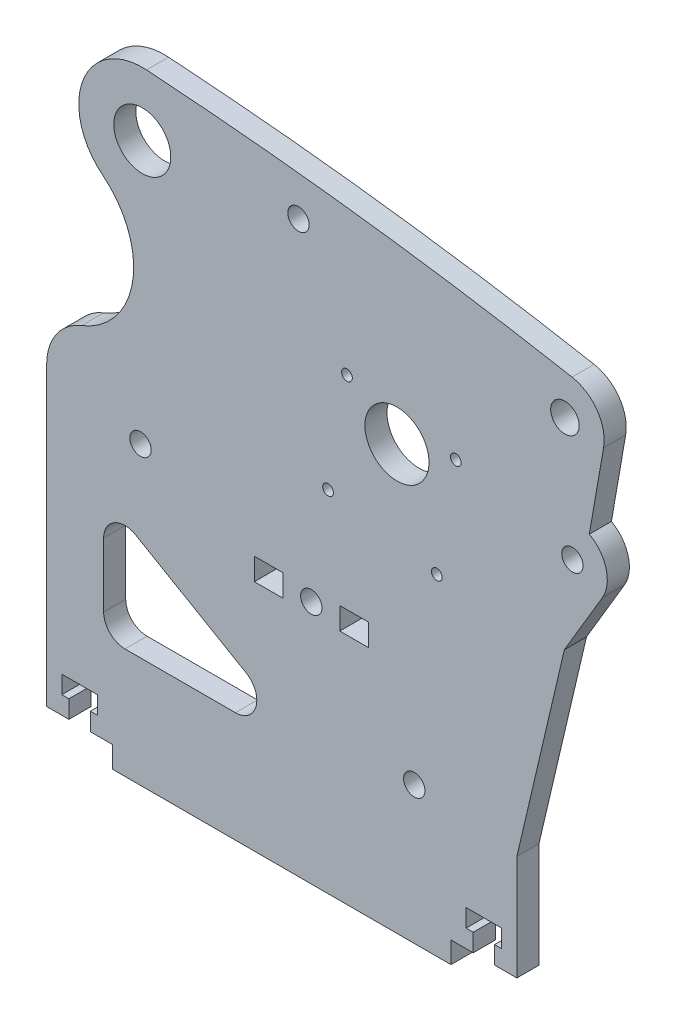
SolidWorks part; units mm, degrees
ref_plane "Front Plane" through (0, 0, 0) normal (0, 0, 1) x (1, 0, 0)
ref_plane "Top Plane" through (0, 0, 0) normal (0, 1, 0) x (1, 0, 0)
ref_plane "Right Plane" through (0, 0, 0) normal (1, 0, 0) x (0, 0, -1)
sketch "Sketch1" plane through (0, 0, 0) normal (0, 0, 1) x (1, 0, 0)
  line L0 (33.65, -83.5) -> (47, -26.5)
  line L1 (-98.35, -29.9005) -> (-98.35, -113)
  line L2 (58, 28.0717) -> (54, 5.0717)
  line L4 (15.15, -113) -> (15.15, -119)
  line L5 (57.6783, -8.5) -> (47, -26.5)
  line L6 (15.15, -119) -> (-79.85, -119)
  line L7 (33.65, -83.5) -> (33.65, -113)
  line L8 (33.65, -113) -> (15.15, -113)
  line L9 (-79.85, -119) -> (-79.85, -113)
  line L10 (-79.85, -113) -> (-98.35, -113)
  line L11 (-79.85, -113) -> (-98.35, -113)
  line L12 (-82.35, -64) -> (-82.35, -82)
  line L13 (-76.35, -88) -> (-45.35, -88)
  line L14 (-42.3372, -76.8113) -> (-73.3372, -58.8113)
  line L20 (57.6783, -8.5) -> (47, -26.5)
  line L22 (33.65, -83.5) -> (33.65, -113)
  line L23 (33.65, -113) -> (15.15, -113)
  line L27 (-82.35, -64) -> (-82.35, -82)
  line L28 (-76.35, -88) -> (-45.35, -88)
  line L29 (-42.3372, -76.8113) -> (-73.3372, -58.8113)
  circle A0 centre (47.15, 30) radius 4
  circle A1 centre (-71.5, 38) radius 8
  circle A2 centre (-71.5, 38) radius 3.5
  circle A3 centre (-27.65, 40.9) radius 3
  circle A4 centre (4.85, -80.4) radius 3
  circle A5 centre (49.25, -3.5) radius 3
  circle A6 centre (-72, -36) radius 3
  circle A7 centre (0, 0) radius 9
  circle A8 centre (0, 0) radius 18.05 construction
  circle A9 centre (47.15, 30) radius 4
  circle A10 centre (-71.5, 38) radius 8
  circle A11 centre (-71.5, 38) radius 3.5
  circle A12 centre (-27.65, 40.9) radius 3
  circle A13 centre (4.85, -80.4) radius 3
  circle A14 centre (49.25, -3.5) radius 3
  circle A15 centre (-72, -36) radius 3
  circle A16 centre (0, 0) radius 9
  circle A17 centre (0, 0) radius 18.05 construction
  arc A18 (58, 28.0717) -> (49.1523, 40.8366) centre (47.15, 30) ccw
  arc A19 (57.6783, -8.5) -> (54, 5.0717) centre (49.25, -3.5) ccw
  arc A21 (-88.5337, -15.4802) -> (-98.35, -29.9005) centre (-82.85, -29.9005) ccw
  arc A22 (-88.5337, -15.4802) -> (-82.6112, 24.0566) centre (-97, 6) ccw
  arc A23 (-70.3185, 55.7899) -> (-82.6112, 24.0566) centre (-71.5, 38) ccw
  arc A24 (-70.3185, 55.7899) -> (49.1523, 40.8366) centre (-138.9064, -976.935) cw
  arc A25 (-73.3372, -58.8113) -> (-82.35, -64) centre (-76.35, -64) ccw
  arc A26 (-82.35, -82) -> (-76.35, -88) centre (-76.35, -82) ccw
  arc A27 (-45.35, -88) -> (-42.3372, -76.8113) centre (-45.35, -82) ccw
  arc A28 (58, 28.0717) -> (49.1523, 40.8366) centre (47.15, 30) ccw
  arc A29 (57.6783, -8.5) -> (54, 5.0717) centre (49.25, -3.5) ccw
  arc A31 (-88.5337, -15.4802) -> (-98.35, -29.9005) centre (-82.85, -29.9005) ccw
  arc A32 (-88.5337, -15.4802) -> (-82.6112, 24.0566) centre (-97, 6) ccw
  arc A33 (-70.3185, 55.7899) -> (-82.6112, 24.0566) centre (-71.5, 38) ccw
  arc A35 (-73.3372, -58.8113) -> (-82.35, -64) centre (-76.35, -64) ccw
  arc A36 (-82.35, -82) -> (-76.35, -88) centre (-76.35, -82) ccw
  arc A37 (-45.35, -88) -> (-42.3372, -76.8113) centre (-45.35, -82) ccw
  point P0 (-98.35, -71.4503)
  dimension "D1" = 18
  dimension "D2" = 47.15
  dimension "D3" = 30
  dimension "D4" = 8
  dimension "D5" = 36
  dimension "D6" = 72
  dimension "D7" = 6
  dimension "D8" = 49.25
  dimension "D9" = 3.5
  dimension "D10" = 40.9
  dimension "D11" = 27.65
  dimension "D12" = 80.4
  dimension "D13" = 4.85
  dimension "D23" = 7
  dimension "D24" = 16
  dimension "D27" = 15.5
  dimension "D32" = 1035
  dimension "D35" = 6
  dimension "D14" = 113
  dimension "D15" = 132
  dimension "D16" = 33.65
  dimension "D17" = 83.5
  dimension "D18" = 47
  dimension "D19" = 57
  dimension "D20" = 83.0995
  dimension "D21" = 71.5
  dimension "D22" = 38
  dimension "D25" = 97
  dimension "D26" = 6
  dimension "D28" = 18
  dimension "D29" = 23
  dimension "D30" = 54
  dimension "D31" = 58
  dimension "D33" = 16
  dimension "D34" = 25
  dimension "D36" = 31
  dimension "D37" = 18
  dimension "D38" = 95
  dimension "D39" = 6
  dimension "D40" = 18.5
extrude "Boss-Extrude1" add sketch "Sketch1" along normal blind 6.2
ref_plane "Plane1" through (-32.35, 0, 0) normal (-1, 0, 0) x (0, 0, 1)
sketch "Sketch2" plane through (0, 0, 6.2) normal (0, 0, 1) x (1, 0, 0)
  circle A0 centre (-19.3487, -20.7923) radius 1.5 construction
  circle A1 centre (11.1929, -26.1038) radius 1.5 construction
  circle A2 centre (-14.0371, 9.7493) radius 1.5 construction
  circle A3 centre (16.5044, 4.4377) radius 1.5 construction
  circle A4 centre (-19.3487, -20.7923) radius 1.5
  circle A5 centre (11.1929, -26.1038) radius 1.5
  circle A6 centre (-14.0371, 9.7493) radius 1.5
  circle A7 centre (16.5044, 4.4377) radius 1.5
extrude "Cut-Extrude1" cut sketch "Sketch2" against normal up to next
sketch "Sketch3" plane through (0, 0, 0) normal (0, 0, -1) x (-1, 0, 0)
  line L0 (-29.4, -103) -> (-19.4, -103)
  line L1 (-29.4, -103) -> (-29.4, -108)
  line L2 (-29.4, -108) -> (-27.4, -108)
  line L3 (-19.4, -103) -> (-19.4, -108)
  line L4 (-33.65, -113) -> (-15.15, -113) construction
  line L10 (-21.4, -108) -> (-19.4, -108)
  line L12 (-27.4, -108) -> (-27.4, -113)
  line L14 (-21.4, -108) -> (-21.4, -113)
  line L15 (-33.65, -83.5) -> (-33.65, -113) construction
  line L16 (-27.4, -113) -> (-21.4, -113)
  line L17 (32.35, -3.3) -> (32.35, 3.3) construction
  line L18 (92.1, -113) -> (86.1, -113)
  line L19 (86.1, -108) -> (86.1, -113)
  line L20 (92.1, -108) -> (92.1, -113)
  line L21 (86.1, -108) -> (84.1, -108)
  line L22 (84.1, -103) -> (84.1, -108)
  line L23 (94.1, -108) -> (92.1, -108)
  line L24 (94.1, -103) -> (94.1, -108)
  line L25 (94.1, -103) -> (84.1, -103)
  dimension "D1" = 5
  dimension "D2" = 5
  dimension "D3" = 10
  dimension "D4" = 6
  dimension "D5" = 6.25
  dimension "D6" = 4.25
extrude "Cut-Extrude2" cut sketch "Sketch3" against normal up to next
sketch "Sketch4" plane through (0, 0, 6.2) normal (0, 0, 1) x (1, 0, 0)
  line L0 (-32.05, -47.3) -> (-32.05, -53.5) construction
  line L1 (-40.05, -53.5) -> (-32.05, -53.5) construction
  line L2 (-40.05, -47.3) -> (-40.05, -53.5) construction
  line L3 (-40.05, -47.3) -> (-32.05, -47.3) construction
  line L4 (-32.05, -47.3) -> (-32.05, -53.5)
  line L5 (-40.05, -53.5) -> (-32.05, -53.5)
  line L6 (-40.05, -47.3) -> (-40.05, -53.5)
  line L7 (-40.05, -47.3) -> (-32.05, -47.3)
  line L8 (-8.05, -47.3) -> (-8.05, -53.5) construction
  line L9 (-16.05, -47.3) -> (-8.05, -47.3) construction
  line L10 (-16.05, -47.3) -> (-16.05, -53.5) construction
  line L11 (-16.05, -53.5) -> (-8.05, -53.5) construction
  line L12 (-8.05, -47.3) -> (-8.05, -53.5)
  line L13 (-16.05, -47.3) -> (-8.05, -47.3)
  line L14 (-16.05, -47.3) -> (-16.05, -53.5)
  line L15 (-16.05, -53.5) -> (-8.05, -53.5)
  line L16 (-16.05, -50.4) -> (-32.05, -50.4) construction
  circle A0 centre (-24.05, -50.4) radius 3
  dimension "D1" = 6
extrude "Cut-Extrude3" cut sketch "Sketch4" against normal up to next
sketch "Sketch5" plane through (0, 0, 0) normal (0, 0, -1) x (-1, 0, 0)
  line L0 (-16.5044, 4.4377) -> (14.0371, 9.7493) construction
  line L1 (-17.9266, 12.615) -> (12.615, 17.9266) construction
  line L2 (-17.9266, 12.615) -> (-12.615, -17.9266) construction
  line L3 (-12.615, -17.9266) -> (17.9266, -12.615) construction
  line L4 (12.615, 17.9266) -> (17.9266, -12.615) construction
  line L5 (-17.9266, 12.615) -> (17.9266, -12.615) construction
  line L6 (-12.615, -17.9266) -> (12.615, 17.9266) construction
  point P0 (0, 0)
  dimension "D1" = 31
  dimension "D2" = 31
